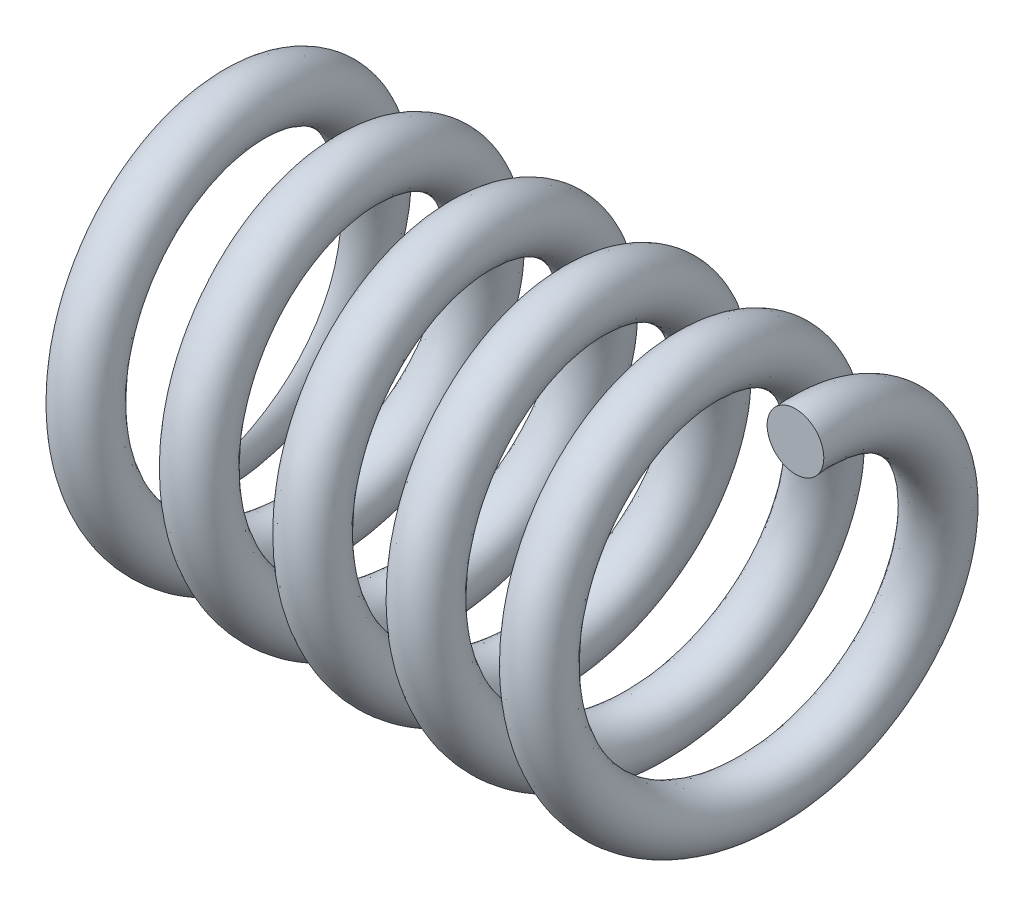
SolidWorks part; units mm, degrees
ref_plane "Plano frontal" through (0, 0, 0) normal (0, 0, 1) x (1, 0, 0)
ref_plane "Plano superior" through (0, 0, 0) normal (0, 1, 0) x (1, 0, 0)
ref_plane "Plano direito" through (0, 0, 0) normal (1, 0, 0) x (0, 0, -1)
sketch "Esboço2" plane through (0, 0, 0) normal (1, 0, 0) x (0, 0, -1)
  circle A0 centre (0, 0) radius 6
  dimension "D1" = 12
curve "Hélice/Espiral1" pitch 4 height 22 turns 5.5
sketch "Esboço3" plane through (0, 0, 0) normal (0, 0, 1) x (1, 0, 0)
  circle A0 centre (0, 6) radius 1
  spline S0 degree 3 poles (0, 6) (-0.0828, 6) (-0.2502, 5.6876) (-0.4999, 4.3531) (-0.75, 2.3559) (-1, 0) (-1.25, -2.3559) (-1.5, -4.3531) (-1.75, -5.6876) (-2, -6.1562) (-2.25, -5.6876) (-2.5, -4.3531) (-2.75, -2.3559) (-3, 0) (-3.25, 2.3559) (-3.5, 4.3531) (-3.75, 5.6876) (-4, 6.1562) (-4.25, 5.6876) (-4.5, 4.3531) (-4.75, 2.3559) (-5, 0) (-5.25, -2.3559) (-5.5, -4.3531) (-5.75, -5.6876) (-6, -6.1562) (-6.25, -5.6876) (-6.5, -4.3531) (-6.75, -2.3559) (-7, 0) (-7.25, 2.3559) (-7.5, 4.3531) (-7.75, 5.6876) (-8, 6.1562) (-8.25, 5.6876) (-8.5, 4.3531) (-8.75, 2.3559) (-9, 0) (-9.25, -2.3559) (-9.5, -4.3531) (-9.75, -5.6876) (-10, -6.1562) (-10.25, -5.6876) (-10.5, -4.3531) (-10.75, -2.3559) (-11, 0) (-11.25, 2.3559) (-11.5, 4.3531) (-11.75, 5.6876) (-12, 6.1562) (-12.25, 5.6876) (-12.5, 4.3531) (-12.75, 2.3559) (-13, 0) (-13.25, -2.3559) (-13.5, -4.3531) (-13.75, -5.6876) (-14, -6.1562) (-14.25, -5.6876) (-14.5, -4.3531) (-14.75, -2.3559) (-15, 0) (-15.25, 2.3559) (-15.5, 4.3531) (-15.75, 5.6876) (-16, 6.1562) (-16.25, 5.6876) (-16.5, 4.3531) (-16.75, 2.3559) (-17, 0) (-17.25, -2.3559) (-17.5, -4.3531) (-17.75, -5.6876) (-18, -6.1562) (-18.25, -5.6876) (-18.5, -4.3531) (-18.75, -2.3559) (-19, 0) (-19.25, 2.3559) (-19.5, 4.3531) (-19.75, 5.6876) (-20, 6.1562) (-20.25, 5.6876) (-20.5, 4.3531) (-20.75, 2.3559) (-21, 0) (-21.25, -2.3559) (-21.5001, -4.3531) (-21.7498, -5.6876) (-21.9172, -6) (-22, -6) knots 0 0 0 0 0.011364 0.022727 0.034091 0.045455 0.056818 0.068182 0.079545 0.090909 0.102273 0.113636 0.125 0.136364 0.147727 0.159091 0.170455 0.181818 0.193182 0.204545 0.215909 0.227273 0.238636 0.25 0.261364 0.272727 0.284091 0.295455 0.306818 0.318182 0.329545 0.340909 0.352273 0.363636 0.375 0.386364 0.397727 0.409091 0.420455 0.431818 0.443182 0.454545 0.465909 0.477273 0.488636 0.5 0.511364 0.522727 0.534091 0.545455 0.556818 0.568182 0.579545 0.590909 0.602273 0.613636 0.625 0.636364 0.647727 0.659091 0.670455 0.681818 0.693182 0.704545 0.715909 0.727273 0.738636 0.75 0.761364 0.772727 0.784091 0.795455 0.806818 0.818182 0.829545 0.840909 0.852273 0.863636 0.875 0.886364 0.897727 0.909091 0.920455 0.931818 0.943182 0.954545 0.965909 0.977273 0.988636 1 1 1 1 construction
  dimension "D1" = 2
sweep "Varredura1" add profiles "Esboço3" path "Hélice/Espiral1"
sketch "Esboço4" plane through (0, 0, 0) normal (0, 0, 1) x (1, 0, 0)
  line L1 (-21.0257, 9.3702) -> (-24.1211, 9.3702)
  line L2 (-21.0257, 9.3702) -> (-21.0257, -8.7917)
  line L3 (-21.0257, -8.7917) -> (-24.1211, -8.7917)
  line L4 (-24.1211, 9.3702) -> (-24.1211, -8.7917)
extrude "Corte-extrusão1" cut sketch "Esboço4" against normal blind 13 and the other way blind 23
